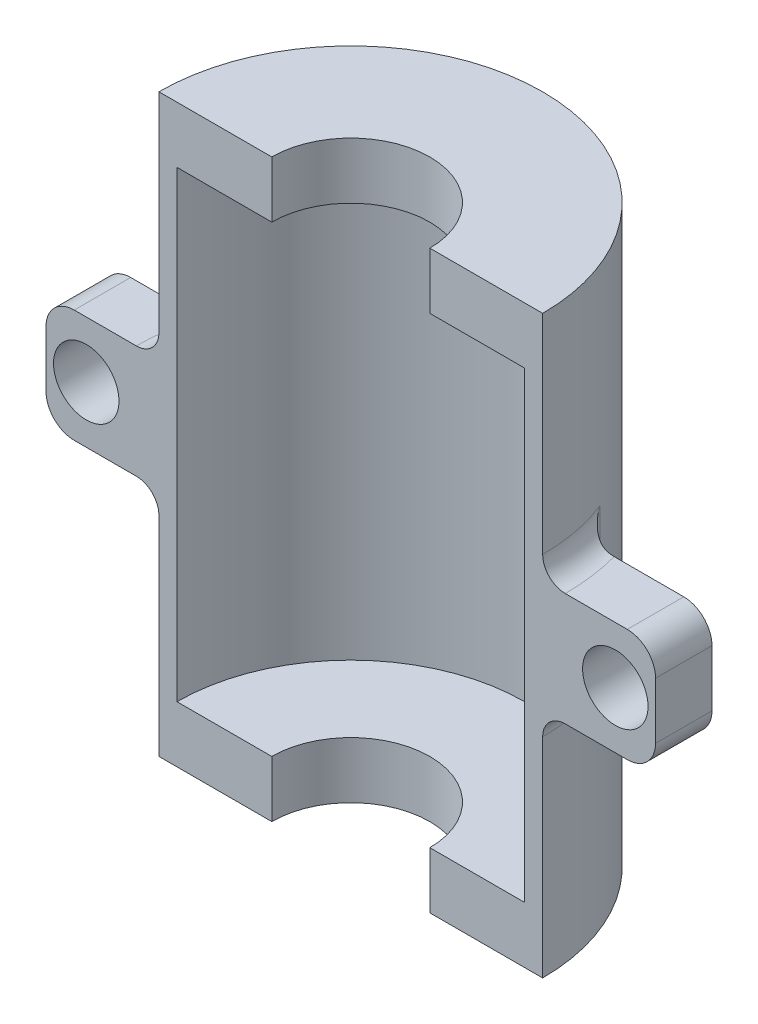
SolidWorks part; units mm, degrees
ref_plane "Front Plane" through (0, 0, 0) normal (0, 0, 1) x (1, 0, 0)
ref_plane "Top Plane" through (0, 0, 0) normal (0, 1, 0) x (1, 0, 0)
ref_plane "Right Plane" through (0, 0, 0) normal (1, 0, 0) x (0, 0, -1)
sketch "Sketch1" plane through (0, 0, 0) normal (0, 1, 0) x (1, 0, 0)
  line L0 (-15.4, 0) -> (-17, 0)
  line L1 (15.4, 0) -> (17, 0)
  circle A0 centre (0, 0) radius 15.4 construction
  circle A1 centre (0, 0) radius 17 construction
  arc A2 (-17, 0) -> (17, 0) centre (0, 0) cw
  arc A3 (-15.4, 0) -> (15.4, 0) centre (0, 0) cw
  dimension "D1" = 30.8
  dimension "D2" = 34
extrude "Boss-Extrude1" add sketch "Sketch1" along normal mid plane 41
sketch "Sketch6" plane through (0, 20.5, 0) normal (0, 1, 0) x (1, 0, 0)
  line L5 (-17, 0) -> (-7, 0)
  line L6 (7, 0) -> (17, 0)
  circle A0 centre (0, 0) radius 7 construction
  arc A2 (-7, 0) -> (7, 0) centre (0, 0) cw
  circle A4 centre (0, 0) radius 17 construction
  arc A5 (-17, 0) -> (17, 0) centre (0, 0) cw
  dimension "D1" = 14
extrude "Boss-Extrude2" add sketch "Sketch6" along normal blind 5
mirror "Mirror1" about plane through (0, 0, 0) normal (0, 1, 0) of "Boss-Extrude2"
sketch "Sketch7" plane through (0, 0, 0) normal (0, 1, 0) x (1, 0, 0)
  line L0 (-17, 0) -> (-27, 0)
  line L1 (-27, 0) -> (-27, 5)
  line L3 (-27, 5) -> (-16.2481, 5)
  arc A2 (17, 0) -> (-17, 0) centre (0, 0) ccw construction
  arc A3 (-16.2481, 5) -> (-17, 0) centre (0, 0) ccw
  point P10 (0, 0)
  point P11 (0, 0)
  dimension "D3" = 17
  dimension "D1" = 5
  dimension "D2" = 10
extrude "Boss-Extrude3" add sketch "Sketch7" along normal mid plane 10
fillet "Fillet1" radius 2 3 edges at (-16.811, -5, -2.5281) (-16.811, 5, -2.5281) (-16.2481, 0, -5)
sketch "Sketch8" plane through (0, 0, -5) normal (0, 0, -1) x (-1, 0, 0)
  circle A0 centre (23.4367, 0) radius 2.9
  dimension "D1" = 5.8
extrude "Cut-Extrude4" cut sketch "Sketch8" against normal mid plane 10
mirror "Mirror3" about plane through (0, 0, 0) normal (1, 0, 0) of "Cut-Extrude4", "Fillet1", "Boss-Extrude3"
fillet "Fillet2" radius 2.5 4 edges at (-27, -5, -2.5) (-27, 5, -2.5) (27, -5, -2.5) (27, 5, -2.5)
